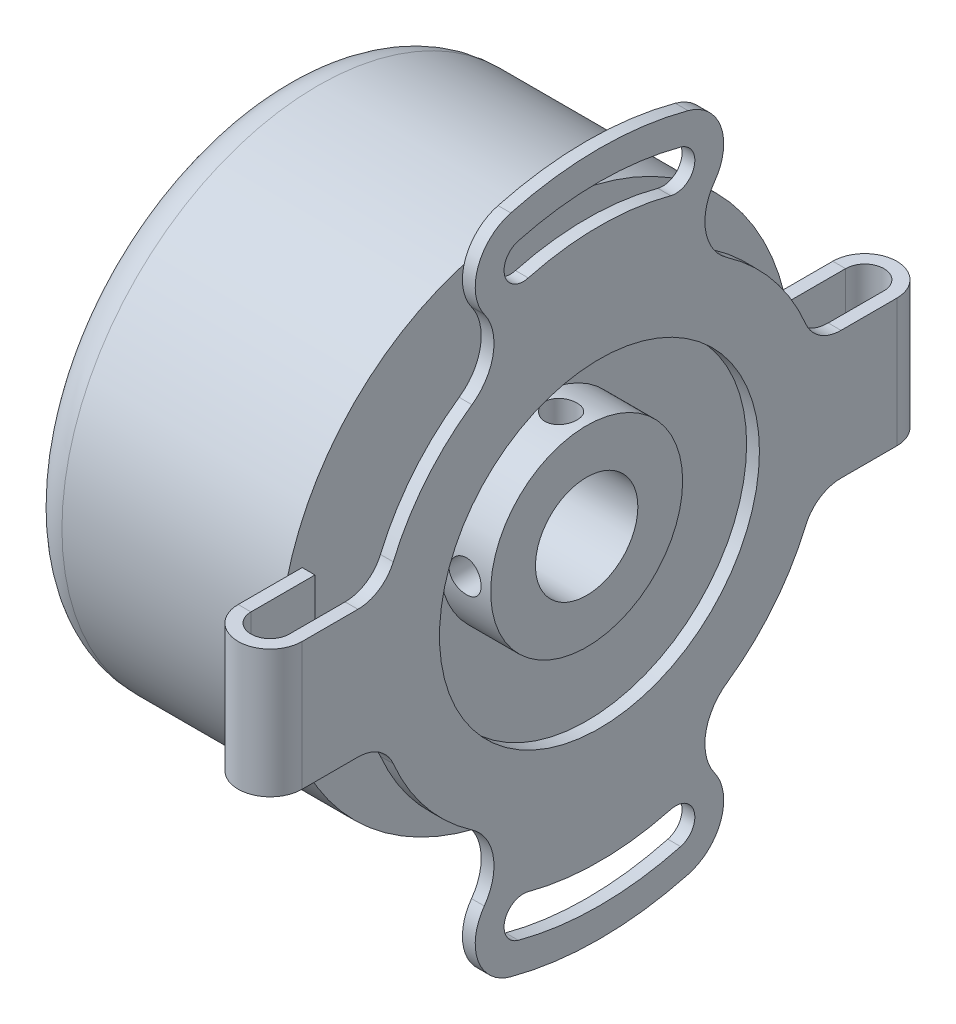
SolidWorks part; units mm, degrees
material "6061 Alloy"
ref_plane "Front Plane" through (0, 0, 0) normal (0, 0, 1) x (1, 0, 0)
ref_plane "Top Plane" through (0, 0, 0) normal (0, 1, 0) x (1, 0, 0)
ref_plane "Right Plane" through (0, 0, 0) normal (1, 0, 0) x (0, 0, -1)
sketch "Sketch1" plane through (0, 0, 0) normal (1, 0, 0) x (0, 0, -1)
  circle A0 centre (0, 0) radius 20
  dimension "D1" = 40
extrude "Boss-Extrude1" add sketch "Sketch1" along normal blind 20
fillet "Fillet1" radius 3 1 edges at (0, 0, -20)
sketch "Sketch2" plane through (20, 0, 0) normal (1, 0, 0) x (0, 0, -1)
  circle A0 centre (0, 0) radius 7.5
  dimension "D1" = 15
extrude "Boss-Extrude2" add sketch "Sketch2" along normal blind 4
hole_wizard "M3x0.5 Tapped Hole1" positions "3DSketch1" profile "Sketch4" tap size "M3x0.5" standard "ANSI Metric"
sketch3d "3DSketch1"
  line L3 (0, 0, 0) -> (28.9691, 0, 0) construction
  point P0 (22, -0.0001, 7.5)
  point P34 (22.0016, 7.5, -0.0002)
sketch "Sketch4" plane through (22, -0.0001, 7.5) normal (1, 0, 0) x (0, -1, 0)
  line L0 (0, 0) -> (0, 8.2511)
  line L1 (0, 8.2511) -> (1.25, 7.5)
  line L2 (1.25, 7.5) -> (1.25, 0)
  line L5 (1.25, 0) -> (0, 0)
  line L10 (0, 8.2511) -> (-1.25, 7.5) construction
  line L11 (0, -6.35) -> (0, 107.95) construction
  dimension "Tap Drill Dia." = 2.5
  dimension "Tap Drill Depth" = 7.5
  dimension "Drill Angle" = 118
cosmetic thread "Hole Thread1" parameters "D1"=6, "D2"=3
cosmetic thread "Hole Thread2" parameters "D1"=6, "D2"=3
sketch "Sketch5" plane through (24, 0, 0) normal (1, 0, 0) x (0, 0, -1)
  circle A0 centre (0, 0) radius 4
  dimension "D1" = 8
extrude "Cut-Extrude1" cut sketch "Sketch5" against normal through all
ref_plane "Plane1" through (25, 0, 0) normal (1, 0, 0) x (0, 0, -1)
sketch "Sketch6" plane through (25, 0, 0) normal (1, 0, 0) x (0, 0, -1)
  line L0 (0, 0) -> (0, 29.3715) construction
  line L1 (0, 0) -> (-6.3411, 23.6652) construction
  line L2 (0, 0) -> (6.3411, 23.6652) construction
  line L3 (0, 0) -> (37.4175, 0) construction
  line L4 (-23.2304, -5) -> (-16.7705, -5)
  line L5 (23.2304, 5) -> (23.2304, -5)
  line L6 (23.2304, -5) -> (16.7705, -5)
  line L7 (16.7705, 5) -> (23.2304, 5)
  line L8 (-23.2304, 5) -> (-23.2304, -5)
  line L9 (-16.7705, 5) -> (-23.2304, 5)
  arc A0 (8.9975, 20.0174) -> (9.963, 14.3871) centre (12.2403, 17.6755) ccw
  circle A2 centre (0, 0) radius 12.5
  arc A3 (5.5646, 20.7674) -> (-5.5646, 20.7674) centre (0, 0) ccw
  arc A4 (6.3411, 23.6652) -> (-6.3411, 23.6652) centre (0, 0) ccw
  arc A5 (9.963, -14.3871) -> (16.7705, -5) centre (0, 0) ccw
  arc A6 (8.9975, 20.0174) -> (6.9249, 25.844) centre (5.9528, 22.2163) ccw
  arc A7 (5.5646, 20.7674) -> (6.3411, 23.6652) centre (5.9528, 22.2163) ccw
  arc A8 (6.9249, 25.844) -> (-6.9249, 25.844) centre (0, 0) ccw
  arc A9 (-5.5646, 20.7674) -> (-6.3411, 23.6652) centre (-5.9528, 22.2163) cw
  arc A10 (16.7705, 5) -> (9.963, 14.3871) centre (0, 0) ccw
  arc A11 (-16.7705, 5) -> (-9.963, 14.3871) centre (0, 0) cw
  arc A12 (-8.9975, 20.0174) -> (-9.963, 14.3871) centre (-12.2403, 17.6755) cw
  arc A13 (-8.9975, 20.0174) -> (-6.9249, 25.844) centre (-5.9528, 22.2163) cw
  arc A14 (6.9249, -25.844) -> (-6.9249, -25.844) centre (0, 0) cw
  arc A15 (-8.9975, -20.0174) -> (-6.9249, -25.844) centre (-5.9528, -22.2163) ccw
  arc A16 (-8.9975, -20.0174) -> (-9.963, -14.3871) centre (-12.2403, -17.6755) ccw
  arc A17 (8.9975, -20.0174) -> (9.963, -14.3871) centre (12.2403, -17.6755) cw
  arc A18 (8.9975, -20.0174) -> (6.9249, -25.844) centre (5.9528, -22.2163) cw
  arc A19 (5.5646, -20.7674) -> (6.3411, -23.6652) centre (5.9528, -22.2163) cw
  arc A20 (6.3411, -23.6652) -> (-6.3411, -23.6652) centre (0, 0) cw
  arc A21 (-5.5646, -20.7674) -> (-6.3411, -23.6652) centre (-5.9528, -22.2163) ccw
  arc A22 (5.5646, -20.7674) -> (-5.5646, -20.7674) centre (0, 0) cw
  arc A23 (16.7705, -5) -> (9.963, -14.3871) centre (0, 0) cw
  arc A24 (-16.7705, -5) -> (-9.963, -14.3871) centre (0, 0) ccw
  dimension "D1" = 1.5
  dimension "D3" = 25
  dimension "D5" = 35
  dimension "D4" = 15
extrude "Boss-Extrude3" add sketch "Sketch6" against normal blind 1 separate body contours L4 A24 A16 A15 A14 A18 A17 A5 L6 L5 L7 A10 A0 A6 A8 A13 A12 A11 L9 L8 A3 A9 A4 A7 A2 A22 A19 A20 A21
fillet "Fillet2" radius 3 4 edges at (24.5, 5, -16.7705) (24.5, -5, -16.7705) (24.5, -5, 16.7705) (24.5, 5, 16.7705)
sketch "Sketch20" plane through (0, 0, 0) normal (0, 1, 0) x (1, 0, 0)
  line L1 (24.5, -23.2304) -> (16.5637, -23.2304) construction
  line L2 (20.5, -21.5) -> (20.5, -24.7917) construction
  line L3 (24, -23.2304) -> (25, -23.2304) construction
  line L4 (20, -20) -> (20, 20) construction
  line L5 (20.5, -23.2304) -> (20.5, -18.2304)
  arc A0 (20.5, -23.2304) -> (24.5, -23.2304) centre (22.5, -23.2304) ccw
  dimension "D1" = 0.5
  dimension "D2" = 5
sketch "Sketch35" plane through (0, 0, 23.2304) normal (0, 0, 1) x (1, 0, 0)
  line L0 (25, -22) -> (25, 22) construction
  line L1 (24, 5) -> (25, 5)
  line L2 (24, 5) -> (24, -5)
  line L3 (24, -5) -> (25, -5)
  line L4 (25, 5) -> (25, -5)
  line L5 (24, -5) -> (25, -5) construction
sweep "Sweep2" add profiles "Sketch35" path "Sketch20"
mirror "Mirror1" about plane through (0, 0, 0) normal (0, 0, 1) of "Sweep2"
